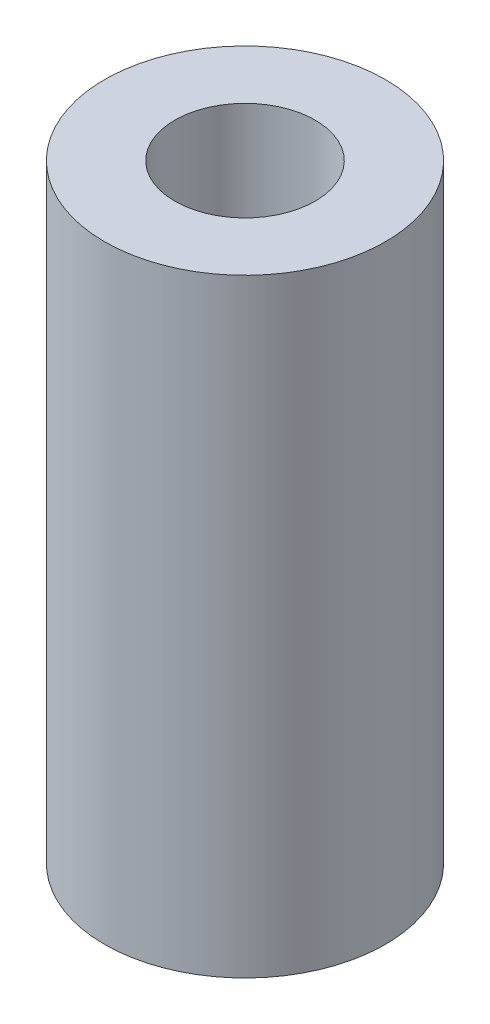
SolidWorks part; units mm, degrees
ref_plane "Front Plane" through (0, 0, 0) normal (0, 0, 1) x (1, 0, 0)
ref_plane "Top Plane" through (0, 0, 0) normal (0, 1, 0) x (1, 0, 0)
ref_plane "Right Plane" through (0, 0, 0) normal (1, 0, 0) x (0, 0, -1)
sketch "Sketch2" plane through (0, 0, 0) normal (0, 1, 0) x (1, 0, 0)
  circle A0 centre (0, 0) radius 3
  circle A1 centre (0, 0) radius 6
  dimension "D1" = 6
  dimension "D2" = 12
extrude "Boss-Extrude1" add sketch "Sketch2" along normal blind 26
